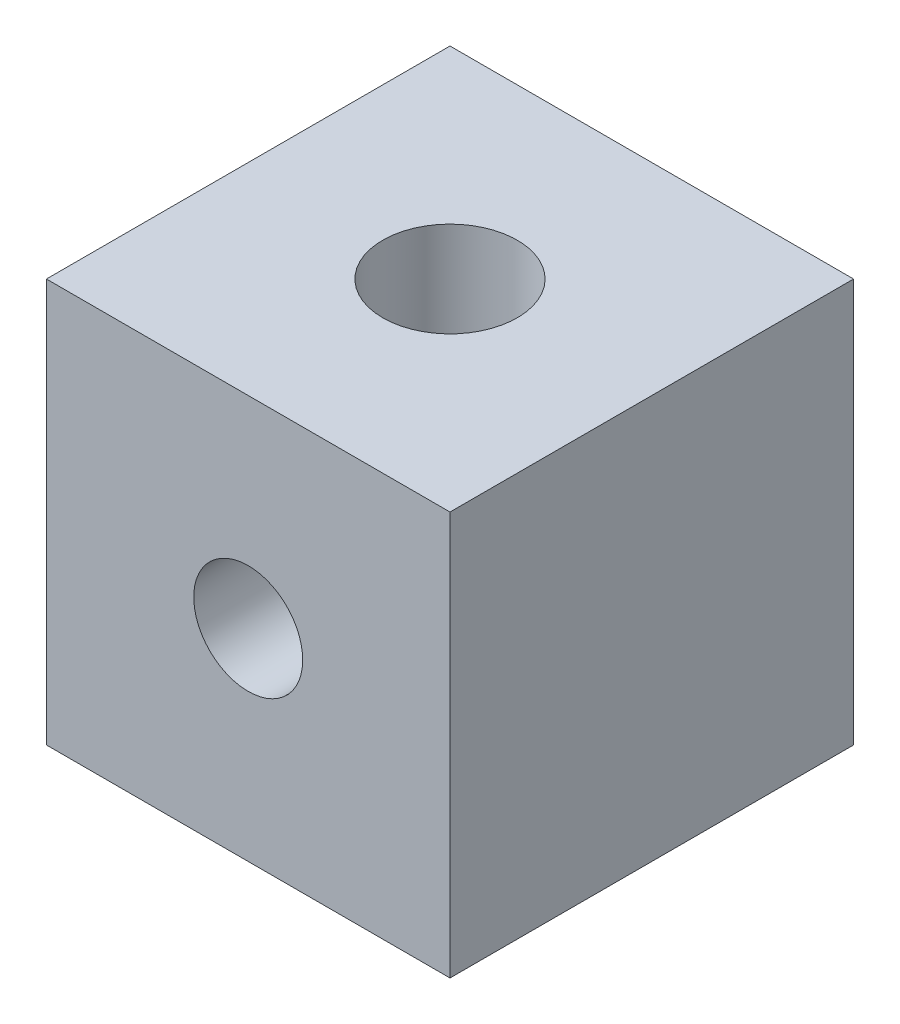
SolidWorks part; units mm, degrees
ref_plane "Front Plane" through (0, 0, 0) normal (0, 0, 1) x (1, 0, 0)
ref_plane "Top Plane" through (0, 0, 0) normal (0, 1, 0) x (1, 0, 0)
ref_plane "Right Plane" through (0, 0, 0) normal (1, 0, 0) x (0, 0, -1)
sketch "Sketch1" plane through (0, 0, 0) normal (0, 0, 1) x (1, 0, 0)
  line L1 (-19.05, 19.05) -> (19.05, 19.05)
  line L2 (-19.05, 19.05) -> (-19.05, -19.05)
  line L3 (-19.05, -19.05) -> (19.05, -19.05)
  line L4 (19.05, 19.05) -> (19.05, -19.05)
  line L5 (-19.05, 19.05) -> (19.05, -19.05) construction
  line L6 (-19.05, -19.05) -> (19.05, 19.05) construction
  point P0 (0, 0)
  dimension "D1" = 38.1
  dimension "D2" = 38.1
extrude "Boss-Extrude1" add sketch "Sketch1" along normal blind 38.1
sketch "Sketch2" plane through (0, 0, 38.1) normal (0, 0, 1) x (1, 0, 0)
  circle A0 centre (0, 0) radius 5.1435
  dimension "D1" = 10.287
extrude "Cut-Extrude1" cut sketch "Sketch2" against normal blind 38.1
sketch "Sketch3" plane through (0, 19.05, 0) normal (0, 1, 0) x (1, 0, 0)
  line L0 (0, 4.7881) -> (0, -39.7412) construction
  line L1 (-20.8461, -19.05) -> (22.203, -19.05) construction
  line L2 (19.05, -38.1) -> (-19.05, -38.1) construction
  circle A0 centre (0, -19.05) radius 6.35
  dimension "D1" = 12.7
  dimension "D2" = 19.05
extrude "Cut-Extrude2" cut sketch "Sketch3" against normal blind 19.05
